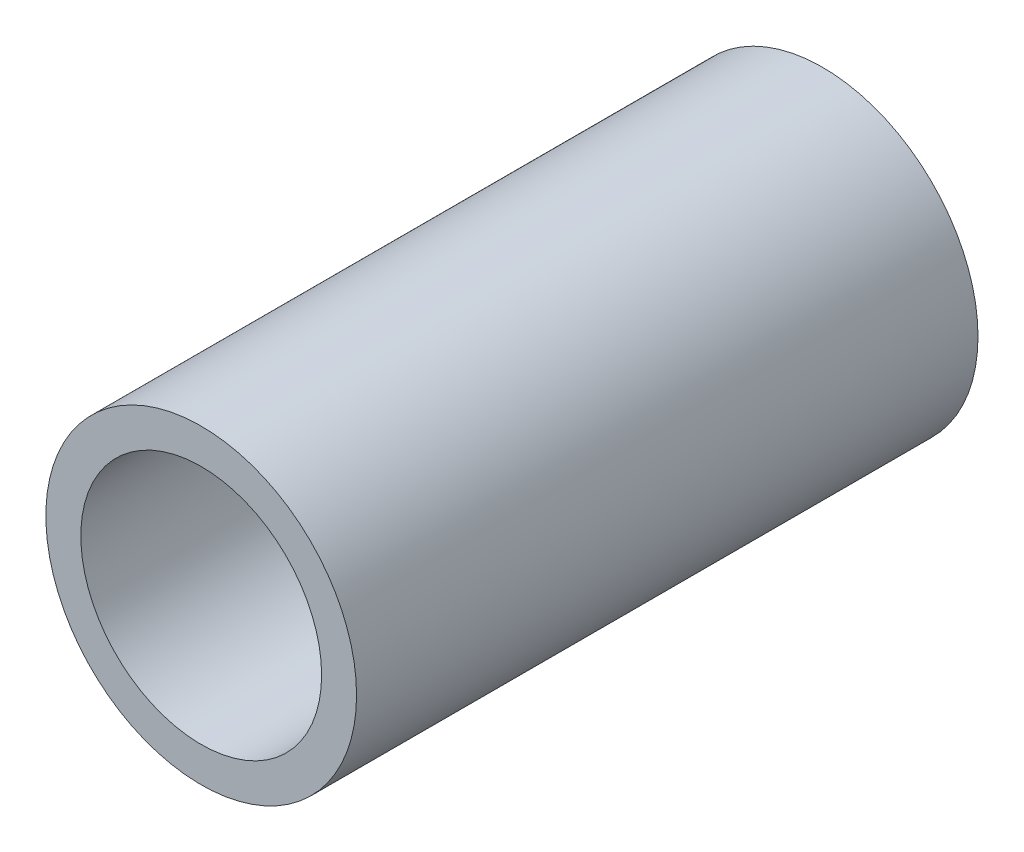
SolidWorks part; units mm, degrees
material "Laiton"
ref_plane "Plan de face" through (0, 0, 0) normal (0, 0, 1) x (1, 0, 0)
ref_plane "Plan de dessus" through (0, 0, 0) normal (0, 1, 0) x (1, 0, 0)
ref_plane "Plan de droite" through (0, 0, 0) normal (1, 0, 0) x (0, 0, -1)
sketch "Esquisse1" plane through (0, 0, 0) normal (0, 0, 1) x (1, 0, 0)
  circle A0 centre (0, 0) radius 1.55
  circle A1 centre (0, 0) radius 2
  dimension "D1" = 3.1
  dimension "D2" = 4
extrude "Boss.-Extru.1" add sketch "Esquisse1" along normal mid plane 8
